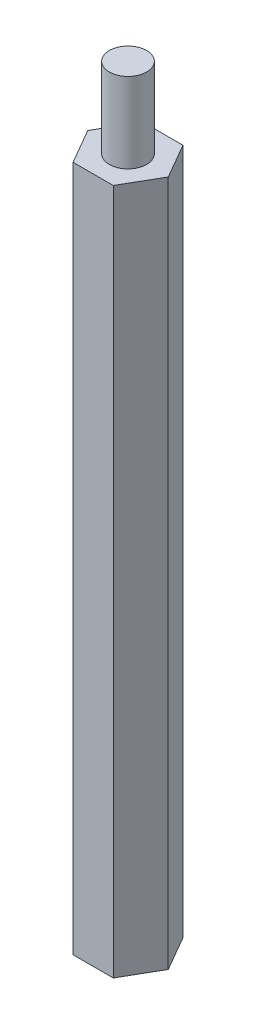
SolidWorks part; units mm, degrees
ref_plane "Front Plane" through (0, 0, 0) normal (0, 0, 1) x (1, 0, 0)
ref_plane "Top Plane" through (0, 0, 0) normal (0, 1, 0) x (1, 0, 0)
ref_plane "Right Plane" through (0, 0, 0) normal (1, 0, 0) x (0, 0, -1)
sketch "Sketch1" plane through (0, 0, 0) normal (0, 1, 0) x (1, 0, 0)
  line L1 (2.9329, 0) -> (1.4665, 2.54)
  line L2 (1.4665, 2.54) -> (-1.4665, 2.54)
  line L3 (-1.4665, 2.54) -> (-2.9329, 0)
  line L4 (-2.9329, 0) -> (-1.4665, -2.54)
  line L5 (-1.4665, -2.54) -> (1.4665, -2.54)
  line L6 (1.4665, -2.54) -> (2.9329, 0)
  circle A0 centre (0, 0) radius 2.54 construction
  dimension "D1" = 5.08
extrude "Boss-Extrude1" add sketch "Sketch1" along normal blind 50.038
sketch "Sketch2" plane through (0, 50.038, 0) normal (0, 1, 0) x (1, 0, 0)
  line L0 (0, 2.54) -> (0, -2.54) construction
  line L1 (-1.4665, -2.54) -> (1.4665, -2.54) construction
  line L2 (1.4665, 2.54) -> (-1.4665, 2.54) construction
  circle A0 centre (0, 0) radius 1.3589
  dimension "D1" = 2.7178
extrude "Boss-Extrude2" add sketch "Sketch2" along normal blind 5.842
sketch "Sketch3" plane through (0, 0, 0) normal (0, -1, 0) x (-1, 0, 0)
  line L0 (-2.1997, -1.27) -> (2.1997, 1.27) construction
  line L1 (1.4665, 2.54) -> (2.9329, 0) construction
  line L2 (-1.4665, -2.54) -> (-2.9329, 0) construction
  circle A0 centre (0, 0) radius 1.3589
  dimension "D1" = 2.7178
extrude "Cut-Extrude1" cut sketch "Sketch3" against normal blind 8.382
